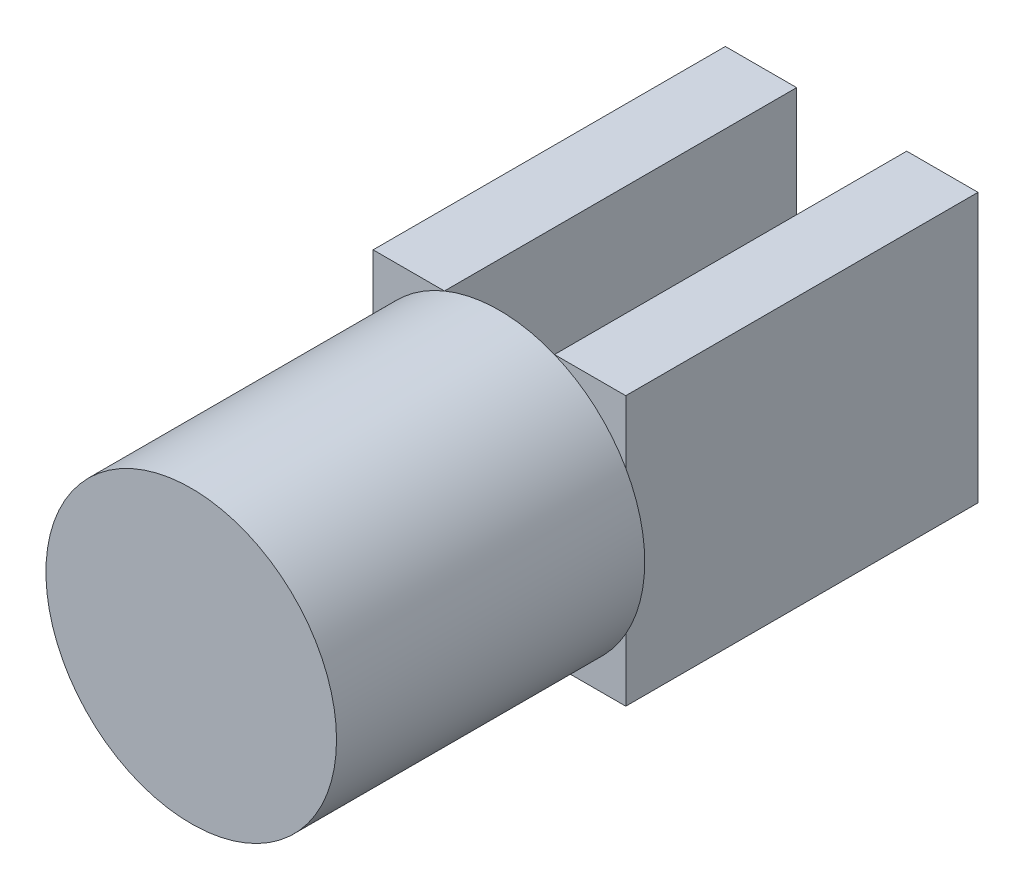
SolidWorks part; units mm, degrees
ref_plane "前视基准面" through (0, 0, 0) normal (0, 0, 1) x (1, 0, 0)
ref_plane "上视基准面" through (0, 0, 0) normal (0, 1, 0) x (1, 0, 0)
ref_plane "右视基准面" through (0, 0, 0) normal (1, 0, 0) x (0, 0, -1)
other "Configuration Table"
sketch "草图1" plane through (0, 0, 0) normal (0, 0, 1) x (1, 0, 0)
  line L0 (0, 33) -> (0, -33) construction
  circle A0 centre (0, 0) radius 33
  dimension "D1" = 66
extrude "凸台-拉伸1" add sketch "草图1" along normal blind 70
sketch "草图2" plane through (0, 0, 0) normal (0, 0, -1) x (-1, 0, 0)
  line L0 (-12.5, 0) -> (12.5, 0) construction
  line L1 (-12.5, 30.541) -> (-12.5, -30.541) construction
  line L2 (12.5, 30.541) -> (12.5, -30.541) construction
  line L3 (0, 0) -> (0, 33) construction
  line L4 (-12.5, 30.541) -> (-28.6906, 30.541)
  line L5 (-12.5, 30.541) -> (-12.5, -30.541)
  line L6 (-12.5, -30.541) -> (-28.6906, -30.541)
  line L7 (-28.6906, 30.541) -> (-28.6906, -30.541)
  line L8 (12.5, 30.541) -> (12.5, -30.541)
  line L9 (12.5, -30.541) -> (28.6906, -30.541)
  line L10 (28.6906, 30.541) -> (28.6906, -30.541)
  line L11 (12.5, 30.541) -> (28.6906, 30.541)
  circle A0 centre (0, 0) radius 12.5
  circle A1 centre (0, 0) radius 33 construction
  dimension "D1" = 25
extrude "凸台-拉伸3" add sketch "草图2" along normal blind 80 contours L4 L7 L6 L5 | L11 L10 L9 L8
